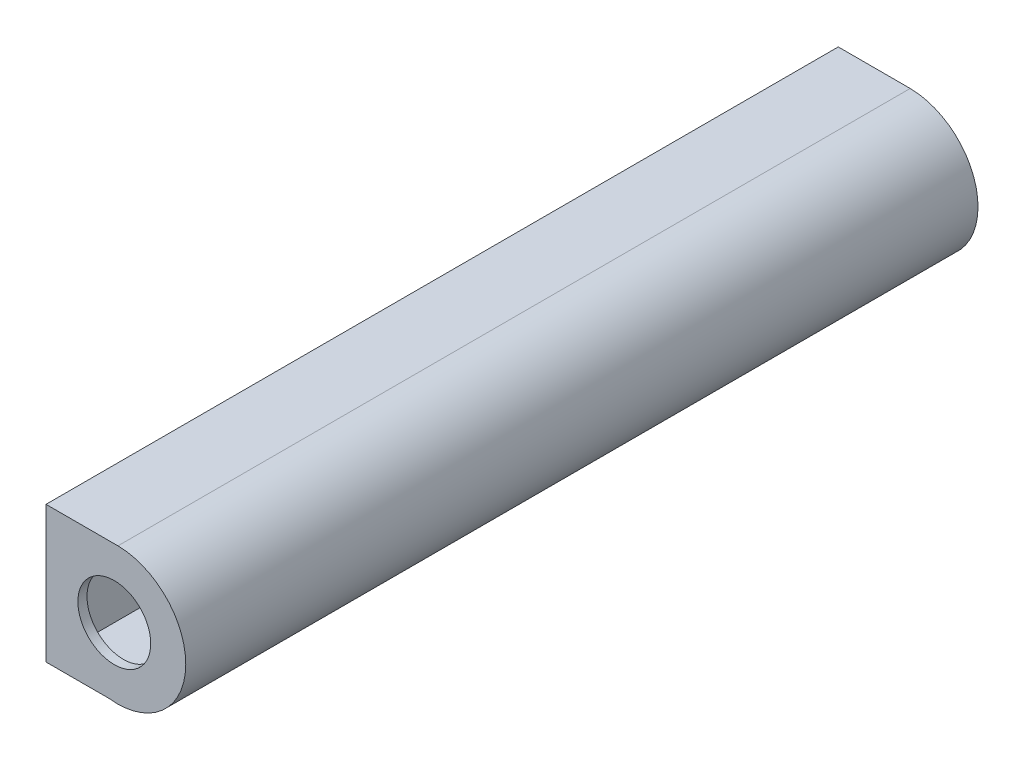
SolidWorks part; units mm, degrees
ref_plane "Alzado" through (0, 0, 0) normal (0, 0, 1) x (1, 0, 0)
ref_plane "Planta" through (0, 0, 0) normal (0, 1, 0) x (1, 0, 0)
ref_plane "Vista lateral" through (0, 0, 0) normal (1, 0, 0) x (0, 0, -1)
sketch "Croquis1" plane through (0, 0, 0) normal (0, 0, 1) x (1, 0, 0)
  line L0 (-12.0775, 12.372) -> (-5.8775, 12.372)
  line L1 (-12.0775, 0.372) -> (-5.8775, 0.372)
  line L2 (-12.0775, 12.372) -> (-12.0775, 0.372)
  line L3 (-5.8775, 13.2513) -> (-5.8775, -0.5073) construction
  line L4 (-5.6757, 13.872) -> (-13.5775, 13.872)
  line L5 (-13.5775, 13.872) -> (-13.5775, -1.128)
  line L6 (-13.5775, -1.128) -> (-6.6931, -1.128)
  arc A0 (-5.8775, 0.372) -> (-5.8775, 12.372) centre (-5.8775, 6.372) ccw
  arc A1 (-5.6757, 13.872) -> (-6.6931, -1.128) centre (-5.7595, 6.3432) cw
  dimension "D1" = 12
  dimension "D2" = 6.2
  dimension "D3" = 1.5
  dimension "D4" = 1.5
  dimension "D5" = 1.5
extrude "Saliente-Extruir1" add sketch "Croquis1" along normal blind 87
sketch "Croquis2" plane through (0, 0, 87) normal (0, 0, 1) x (1, 0, 0)
  line L0 (-13.5775, 6.372) -> (6.6804, 6.372) construction
  line L1 (-13.5775, 13.872) -> (-13.5775, -1.128) construction
  line L2 (-12.0775, 12.372) -> (-12.0775, 0.372) construction
  line L3 (-13.5775, 13.872) -> (-13.5775, -1.128)
  line L4 (-13.5775, -1.128) -> (-4.8258, -1.128)
  line L5 (-13.5775, 13.872) -> (-5.6757, 13.872)
  line L6 (-5.6757, 13.872) -> (-13.5775, 13.872) construction
  line L7 (-13.5775, -1.128) -> (-6.6931, -1.128) construction
  circle A0 centre (-6.0775, 6.372) radius 4
  arc A4 (-5.6757, 13.872) -> (-4.8258, -1.128) centre (-5.7595, 6.3432) cw
  arc A5 (-6.6931, -1.128) -> (-5.6757, 13.872) centre (-5.7595, 6.3432) ccw construction
  point P2 (-7.0775, 6.372)
  point P15 (-7.0775, 6.372)
  dimension "D1" = 8
  dimension "D2" = 6
extrude "Saliente-Extruir2" add sketch "Croquis2" against normal blind 1
